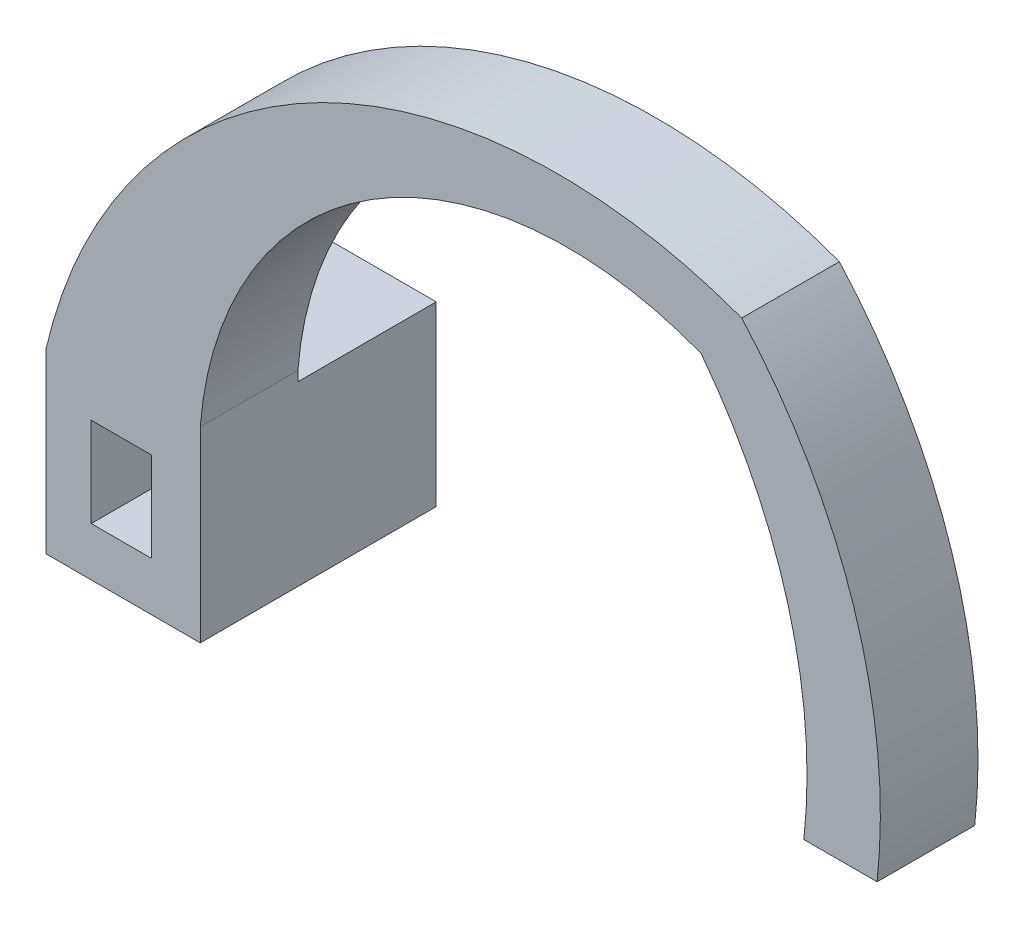
SolidWorks part; units mm, degrees
ref_plane "Front Plane" through (0, 0, 0) normal (0, 0, 1) x (1, 0, 0)
ref_plane "Top Plane" through (0, 0, 0) normal (0, 1, 0) x (1, 0, 0)
ref_plane "Right Plane" through (0, 0, 0) normal (1, 0, 0) x (0, 0, -1)
sketch "Sketch1" plane through (0, 0, 0) normal (0, 0, 1) x (1, 0, 0)
  line L1 (-1.85, 2.75) -> (1.85, 2.75)
  line L2 (-1.85, 2.75) -> (-1.85, -2.75)
  line L3 (-1.85, -2.75) -> (1.85, -2.75)
  line L4 (1.85, 2.75) -> (1.85, -2.75)
  line L6 (4.85, 5.75) -> (4.85, -5.75)
  line L7 (4.85, -5.75) -> (-4.629, -5.75)
  line L8 (-4.629, -5.75) -> (-4.629, 5.1487)
  line L18 (41.939, 2.3297) -> (46.4408, 2.3297)
  arc A8 (4.85, 5.75) -> (35.6199, 25.0444) centre (27.4227, 3.9345) cw
  arc A10 (46.4408, 2.3297) -> (38.1232, 28.1736) centre (13.4632, 5.9766) ccw
  arc A11 (41.939, 2.3297) -> (35.6199, 25.0444) centre (10.5958, 5.8465) ccw
  arc A12 (-4.629, 5.1487) -> (38.1232, 28.1736) centre (26.8654, -2.1264) cw
  point P4 (0, 2.75)
  point P6 (-1.85, 0)
  dimension "D1" = 5.5
  dimension "D2" = 3.7
  dimension "D3" = 41.939
  dimension "D4" = 3
  dimension "D5" = 3
  dimension "D6" = 19.2944
  dimension "D7" = 6.3191
extrude "Boss-Extrude1" add sketch "Sketch1" along normal blind 6
sketch "Sketch2" plane through (0, 0, 6) normal (0, 0, 1) x (1, 0, 0)
  line L0 (0, 2.75) -> (0, -2.75) construction
  line L1 (1.85, 2.75) -> (-1.85, 2.75) construction
  line L2 (-1.85, -2.75) -> (1.85, -2.75) construction
  line L3 (-1.85, 0) -> (1.85, 0) construction
  line L4 (-1.85, 2.75) -> (-1.85, -2.75) construction
  line L5 (1.85, -2.75) -> (1.85, 2.75) construction
sketch "Sketch3" plane through (0, 0, 0) normal (0, 0, 1) x (1, 0, 0)
  line L1 (-4.629, -5.75) -> (4.85, -5.75)
  line L2 (-4.629, -5.75) -> (-4.629, 5.1487)
  line L3 (-4.629, 5.1487) -> (4.85, 5.1487)
  line L4 (4.85, -5.75) -> (4.85, 5.1487)
  line L5 (-1.85, 2.75) -> (1.85, 2.75)
  line L6 (-1.85, 2.75) -> (-1.85, -2.75)
  line L7 (-1.85, -2.75) -> (1.85, -2.75)
  line L8 (1.85, 2.75) -> (1.85, -2.75)
  point P12 (0, 0)
extrude "Boss-Extrude2" add sketch "Sketch3" against normal blind 8.5
